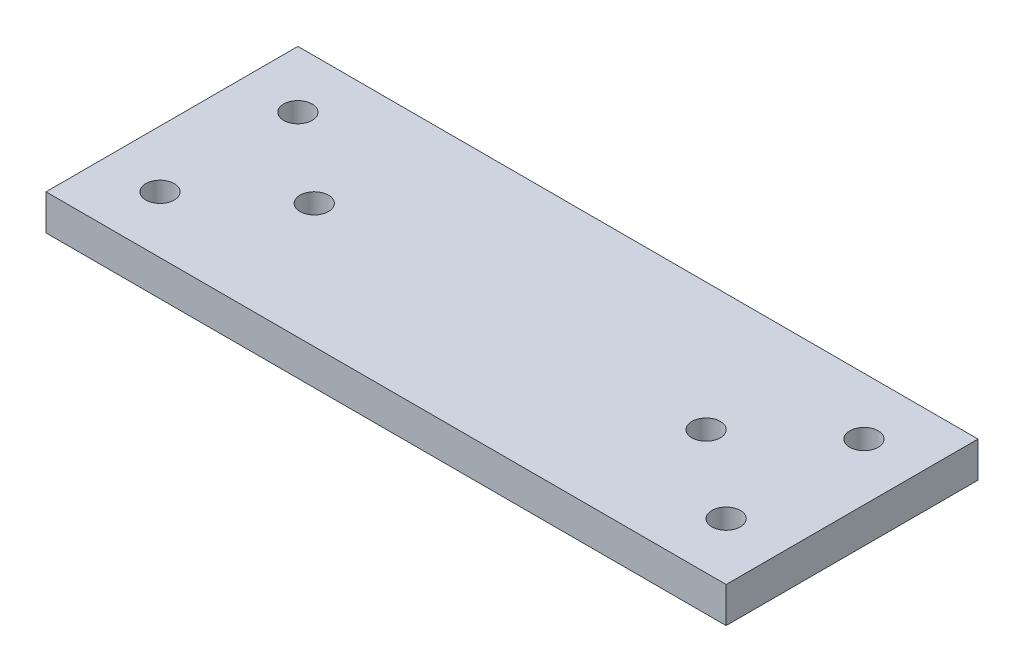
SolidWorks part; units mm, degrees
ref_plane "前视基准面" through (0, 0, 0) normal (0, 0, 1) x (1, 0, 0)
ref_plane "上视基准面" through (0, 0, 0) normal (0, 1, 0) x (1, 0, 0)
ref_plane "右视基准面" through (0, 0, 0) normal (1, 0, 0) x (0, 0, -1)
sketch "草图1" plane through (0, 0, 0) normal (0, 1, 0) x (1, 0, 0)
  line L1 (-39.1961, 15.1951) -> (56.2539, 15.1951)
  line L2 (-39.1961, 15.1951) -> (-39.1961, -20.1549)
  line L3 (-39.1961, -20.1549) -> (56.2539, -20.1549)
  line L4 (56.2539, 15.1951) -> (56.2539, -20.1549)
  line L5 (-34.1961, 10.1951) -> (51.2539, 10.1951) construction
  line L6 (-34.1961, 10.1951) -> (-34.1961, -15.1549) construction
  line L7 (-34.1961, -15.1549) -> (51.2539, -15.1549) construction
  line L8 (51.2539, 10.1951) -> (51.2539, -15.1549) construction
  line L9 (-31.1961, 7.1951) -> (48.2539, 7.1951) construction
  line L10 (-31.1961, 7.1951) -> (-31.1961, -12.1549) construction
  line L11 (-31.1961, -12.1549) -> (48.2539, -12.1549) construction
  line L12 (48.2539, 7.1951) -> (48.2539, -12.1549) construction
  circle A0 centre (-31.1961, 7.1951) radius 2
  circle A1 centre (-31.1961, -12.1549) radius 2
  circle A2 centre (48.2539, 7.1951) radius 2
  circle A3 centre (48.2539, -12.1549) radius 2
  point P12 (8.5289, 7.1951)
  point P13 (8.5289, 10.1951)
  point P14 (8.5289, 15.1951)
  point P15 (-39.1961, -2.4799)
  point P16 (-34.1961, -2.4799)
  point P17 (-31.1961, -2.4799)
  dimension "D5" = 5
  dimension "D1" = 25.35
  dimension "D2" = 85.45
  dimension "D3" = 3
  dimension "D4" = 3
  dimension "D6" = 5
extrude "凸台-拉伸1" add sketch "草图1" along normal blind 5
sketch "草图2" plane through (0, 5, 0) normal (0, 1, 0) x (1, 0, 0)
  line L0 (-18.9711, -2.7352) -> (36.0289, -2.7352) construction
  line L1 (56.2539, 15.1951) -> (-39.1961, 15.1951) construction
  circle A0 centre (-18.9711, -2.7352) radius 2
  circle A1 centre (36.0289, -2.7352) radius 2
  point P2 (8.5289, -2.7352)
  point P3 (8.5289, 15.1951)
  dimension "D1" = 55
extrude "切除-拉伸1" cut sketch "草图2" against normal blind 5
